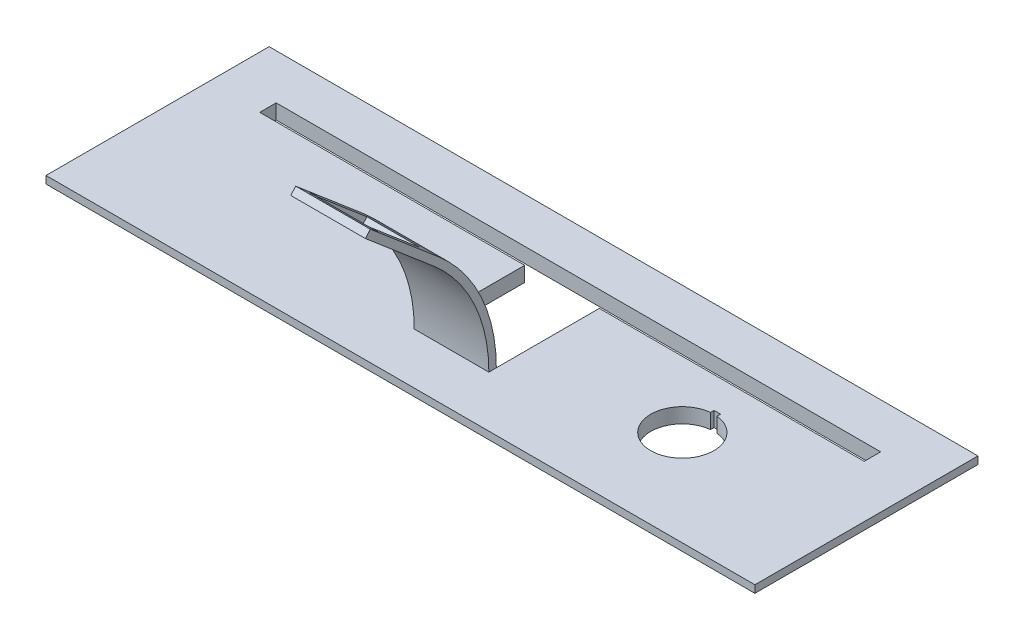
SolidWorks part; units mm, degrees
ref_plane "Front" through (0, 0, 0) normal (0, 0, 1) x (1, 0, 0)
ref_plane "Top" through (0, 0, 0) normal (0, 1, 0) x (1, 0, 0)
ref_plane "Right" through (0, 0, 0) normal (1, 0, 0) x (0, 0, -1)
sketch "Sketch1" plane through (0, 0, 0) normal (0, 1, 0) x (1, 0, 0)
  line L1 (-117.475, 34.798) -> (117.475, 34.798)
  line L2 (-117.475, 34.798) -> (-117.475, -34.798)
  line L3 (-117.475, -34.798) -> (117.475, -34.798)
  line L4 (117.475, 34.798) -> (117.475, -34.798)
  line L5 (-117.475, 34.798) -> (117.475, -34.798) construction
  line L6 (-117.475, -34.798) -> (117.475, 34.798) construction
  point P0 (0, 0)
  dimension "D1" = 69.596
  dimension "D2" = 234.95
extrude "Boss-Extrude1" add sketch "Sketch1" along normal blind 2.54
sketch "Sketch2" plane through (0, 2.54, 0) normal (0, 1, 0) x (1, 0, 0)
  line L8 (120.65, -37.973) -> (120.65, 37.973)
  line L9 (120.65, 37.973) -> (-120.65, 37.973)
  line L10 (-120.65, 37.973) -> (-120.65, -37.973)
  line L11 (-120.65, -37.973) -> (120.65, -37.973)
  line L12 (120.65, -37.973) -> (120.65, 37.973)
  line L13 (120.65, 37.973) -> (-120.65, 37.973)
  line L14 (-120.65, 37.973) -> (-120.65, -37.973)
  line L15 (-120.65, -37.973) -> (120.65, -37.973)
  dimension "D1" = 3.175
extrude "Boss-Extrude2" add sketch "Sketch2" along normal blind 2.54
sketch "Sketch3" plane through (0, 5.08, 0) normal (0, 1, 0) x (1, 0, 0)
  line L1 (-102.87, 22.606) -> (102.87, 22.606)
  line L2 (-102.87, 22.606) -> (-102.87, 12.446)
  line L3 (-102.87, 12.446) -> (102.87, 12.446)
  line L4 (102.87, 22.606) -> (102.87, 12.446)
  line L5 (120.65, 37.973) -> (-120.65, 37.973) construction
  line L6 (-12.7, 17.018) -> (-12.7, 12.446)
  line L7 (-102.87, 17.018) -> (102.87, 17.018)
  line L8 (-102.87, 17.018) -> (-102.87, 22.606)
  line L9 (-102.87, 22.606) -> (102.87, 22.606)
  line L10 (102.87, 17.018) -> (102.87, 22.606)
  line L11 (-12.7, 12.446) -> (12.7, 12.446)
  line L12 (-12.7, 12.446) -> (-12.7, -18.034)
  line L13 (0, -31.2408) -> (0, 31.2408) construction
  line L14 (12.7, 17.018) -> (12.7, 12.446)
  line L15 (-12.7, -18.034) -> (12.7, -18.034)
  line L16 (12.7, 12.446) -> (12.7, -18.034)
  point P0 (0, 0)
  point P8 (0, 0)
  dimension "D1" = 205.74
  dimension "D2" = 10.16
  dimension "D3" = 15.367
  dimension "D4" = 25.4
  dimension "D5" = 4.572
  dimension "D6" = 30.48
extrude "Cut-Extrude2" cut sketch "Sketch3" against normal through all contours L2 L7 L4 L1 | L14 L7 L6 L3 | L16 L3 L12 L15
sketch "Sketch4" plane through (0, 0, 0) normal (1, 0, 0) x (0, 0, -1)
  line L0 (22.606, 5.08) -> (17.018, 5.08) construction
  line L1 (22.606, 5.08) -> (17.018, 5.08)
  line L2 (-37.7211, 47.6552) -> (-39.3663, 45.72)
  line L4 (-37.973, 2.54) -> (37.973, 2.54)
  line L5 (37.973, 2.54) -> (37.973, 5.08)
  line L6 (37.973, 5.08) -> (-37.973, 5.08)
  line L7 (-37.973, 5.08) -> (-37.973, 2.54)
  line L8 (-37.973, 2.54) -> (37.973, 2.54)
  line L9 (37.973, 2.54) -> (37.973, 5.08)
  line L10 (37.973, 5.08) -> (-37.973, 5.08)
  line L11 (-37.973, 5.08) -> (-37.973, 2.54)
  line L14 (17.018, 5.08) -> (-18.034, 5.08)
  line L15 (-18.034, 5.08) -> (-18.034, 0)
  line L16 (-18.034, 0) -> (17.018, 0)
  line L17 (17.018, 0) -> (17.018, 5.08)
  line L18 (17.018, 5.08) -> (-18.034, 5.08)
  line L20 (-18.034, 0) -> (17.018, 0)
  line L21 (17.018, 0) -> (17.018, 5.08)
  line L23 (-18.034, 5.08) -> (-18.034, 0)
  arc A0 (-18.034, 5.08) -> (-37.7211, 47.6552) centre (-73.914, 5.08) ccw
  arc A1 (-20.574, 5.08) -> (-39.3663, 45.72) centre (-73.914, 5.08) ccw
  dimension "2" = 53.34
  dimension "D5" = 40.64
  dimension "D1" = 0
  dimension "D2" = 0
  dimension "D3" = 2.54
extrude "Boss-Extrude7" add sketch "Sketch4" along normal blind 12.7 and the other way blind 12.7 contours A1 L10 A0 L2
sketch "Sketch5" plane through (0, 38.606, 45.4139) normal (0, 0.6477, 0.7619) x (1, 0, 0)
  line L4 (-12.7, 9.3372) -> (12.7, 9.3372)
  line L5 (12.7, 9.3372) -> (12.7, 11.8772)
  line L6 (12.7, 11.8772) -> (-12.7, 11.8772)
  line L7 (-12.7, 11.8772) -> (-12.7, 9.3372)
  line L8 (-12.7, 9.3372) -> (12.7, 9.3372)
  line L9 (12.7, 9.3372) -> (12.7, 11.8772)
  line L10 (12.7, 11.8772) -> (-12.7, 11.8772)
  line L11 (-12.7, 11.8772) -> (-12.7, 9.3372)
  dimension "D1" = 0
extrude "Boss-Extrude8" add sketch "Sketch5" along normal blind 30.48
sketch "Sketch6" plane through (0, 9.0493, -7.6927) normal (0, 0.7619, -0.6477) x (1, 0, 0)
  line L0 (0, -31.2408) -> (0, 31.2408) construction
  line L1 (-9.144, -62.9463) -> (9.144, -62.9463)
  line L2 (-9.144, -62.9463) -> (-9.144, -85.9651)
  line L3 (-9.144, -85.9651) -> (9.144, -85.9651)
  line L4 (12.7, -59.6057) -> (-12.7, -59.6057)
  line L5 (-12.7, -59.6057) -> (-12.7, -90.0857)
  line L6 (-12.7, -90.0857) -> (12.7, -90.0857)
  line L7 (12.7, -90.0857) -> (12.7, -59.6057)
  line L8 (12.7, -59.6057) -> (-12.7, -59.6057)
  line L9 (-12.7, -59.6057) -> (-12.7, -90.0857)
  line L10 (-12.7, -90.0857) -> (12.7, -90.0857)
  line L11 (12.7, -90.0857) -> (12.7, -59.6057)
  line L12 (9.144, -62.9463) -> (9.144, -85.9651)
  line L13 (-9.144, -62.9463) -> (9.144, -85.9651) construction
  line L14 (-9.144, -85.9651) -> (9.144, -62.9463) construction
  point P2 (0, -74.4557)
  dimension "D2" = 18.288
  dimension "D3" = 23.0188
  dimension "D1" = 0
extrude "Cut-Extrude3" cut sketch "Sketch6" against normal up to next contours L12 L1 L2 L3
sketch "Sketch9" plane through (0, 9.0493, -7.6927) normal (0, 0.7619, -0.6477) x (1, 0, 0)
  line L0 (0, -31.2408) -> (0, 31.2408) construction
  line L2 (-9.144, -62.9463) -> (9.144, -62.9463) construction
  circle A0 centre (-10.3187, -85.1713) radius 1
  circle A1 centre (10.3187, -85.1713) radius 1
  dimension "D3" = 2
  dimension "D1" = 22.225
  dimension "D2" = 20.6375
extrude "Cut-Extrude4" cut sketch "Sketch9" against normal up to next
sketch "Sketch10" plane through (0, 5.08, 0) normal (0, 1, 0) x (1, 0, 0)
  line L0 (63.4007, -5.4213) -> (63.4007, 10.0321) construction
  line L1 (62.3007, 6.4723) -> (64.5007, 6.4723)
  line L2 (64.5007, 6.4723) -> (64.5007, 5.2723)
  line L3 (62.3007, 6.4723) -> (62.3007, 5.2723)
  arc A0 (62.3007, 5.2723) -> (64.5007, 5.2723) centre (63.4007, -5.4213) ccw
  point P8 (63.4007, 6.4723)
  dimension "D1" = 21.5
  dimension "D2" = 1.1
  dimension "D3" = 1.2
extrude "Cut-Extrude6" cut sketch "Sketch10" against normal up to next
